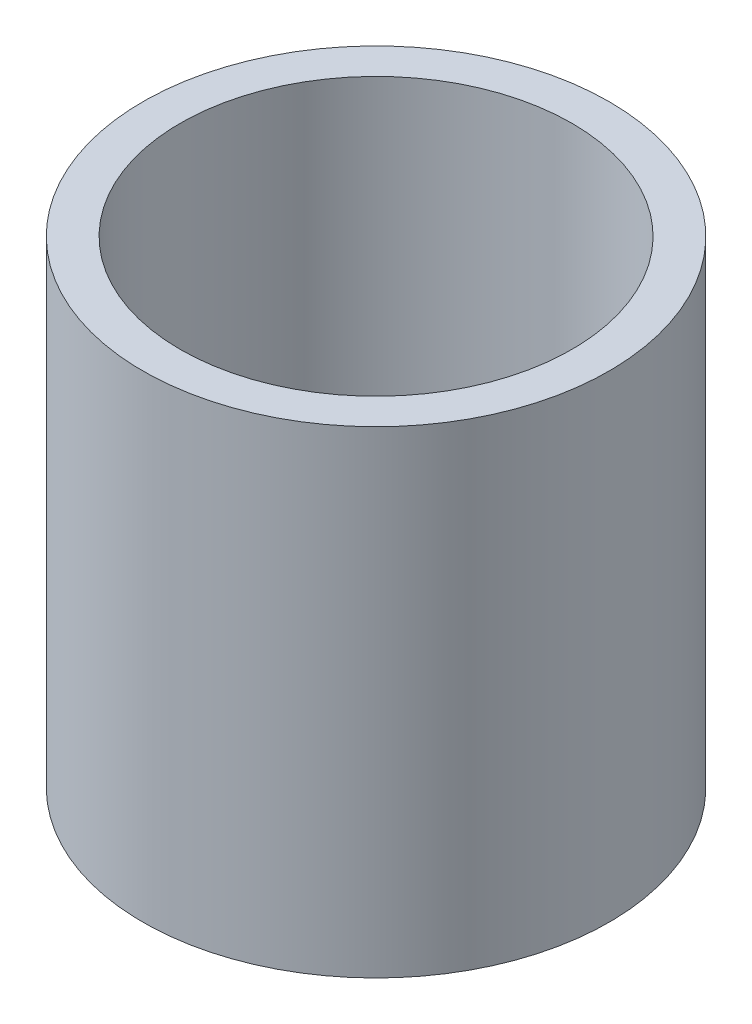
SolidWorks part; units mm, degrees
material "3003 Alloy"
ref_plane "Front Plane" through (0, 0, 0) normal (0, 0, 1) x (1, 0, 0)
ref_plane "Top Plane" through (0, 0, 0) normal (0, 1, 0) x (1, 0, 0)
ref_plane "Right Plane" through (0, 0, 0) normal (1, 0, 0) x (0, 0, -1)
sketch "Sketch1" plane through (0, 0, 0) normal (0, 1, 0) x (1, 0, 0)
  circle A0 centre (0, 0) radius 2.667
  circle A1 centre (0, 0) radius 3.175
  dimension "D1" = 6.35
  dimension "D2" = 5.334
extrude "Boss-Extrude1" add sketch "Sketch1" along normal blind 6.5
move or copy body "Body-Move/Copy1" [suppressed] bodies to move or copy 101
